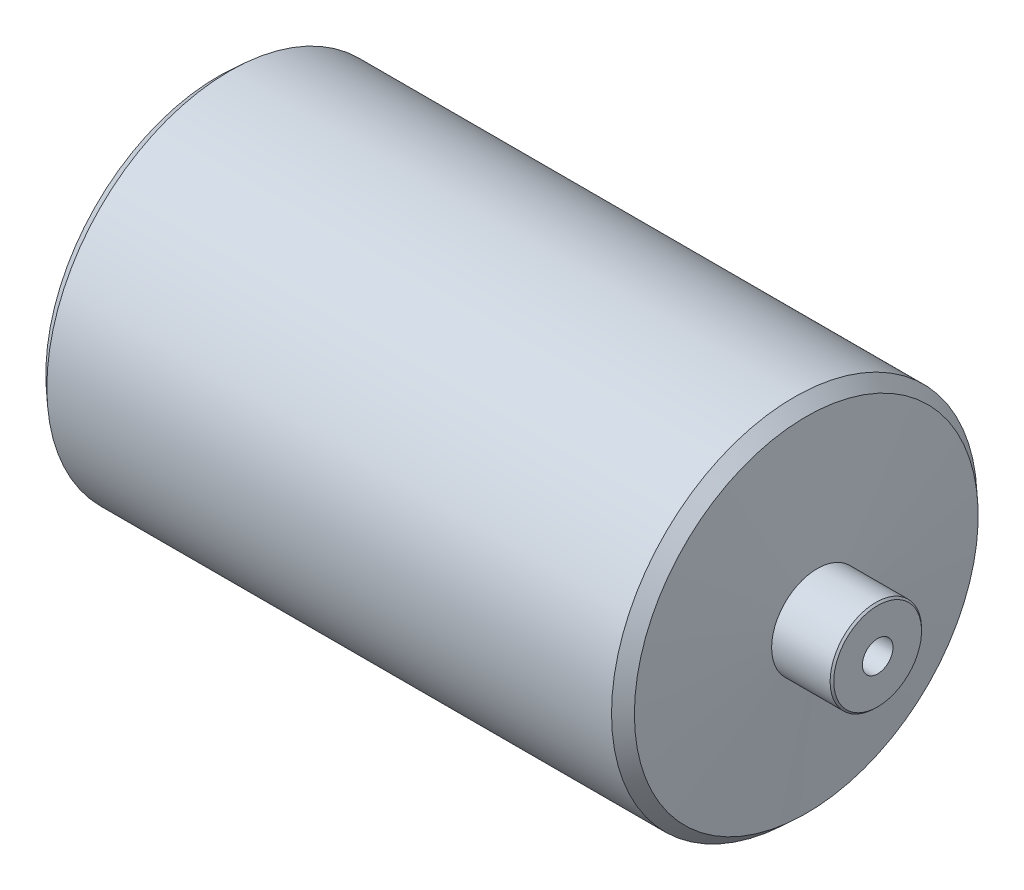
SolidWorks part; units mm, degrees
ref_plane "前基準面" through (0, 0, 0) normal (0, 0, 1) x (1, 0, 0)
ref_plane "上基準面" through (0, 0, 0) normal (0, 1, 0) x (1, 0, 0)
ref_plane "右基準面" through (0, 0, 0) normal (1, 0, 0) x (0, 0, -1)
ref_plane "平面1"
sketch "草圖1" plane through (0, 0, 0) normal (0, 0, 1) x (1, 0, 0)
  line L0 (0, 0) -> (0, 12.5)
  line L1 (0, 12.5) -> (16.5, 12.5)
  line L2 (16.5, 12.5) -> (19.7808, 50)
  line L3 (19.7808, 50) -> (180.2192, 50)
  line L4 (180.2192, 50) -> (183.5, 12.5)
  line L5 (183.5, 12.5) -> (200, 12.5)
  line L6 (200, 12.5) -> (200, 0)
  line L7 (200, 0) -> (0, 0)
  line L8 (0, 0) -> (200, 0) construction
  dimension "D1" = 12.5
  dimension "D2" = 200
  dimension "D3" = 12.5
  dimension "D4" = 16.5
  dimension "D5" = 16.5
  dimension "D6" = 95
  dimension "D7" = 95
  dimension "D8" = 50
revolve "迴轉1" add sketch "草圖1" angle 360 about L8
chamfer "倒角1" distance 3 distance2 3 2 edges at (180.2192, 0, 50) (19.7808, 0, 50)
chamfer "倒角2" distance 0.5 distance2 0.5 2 edges at (200, 0, 12.5) (0, 0, 12.5)
hole_wizard "孔1" positions "草圖3" profile "草圖2" legacy
sketch "草圖3" plane through (200, 0, 0) normal (1, 0, 0) x (0, 0, -1)
  point P1 (0, 0)
sketch "草圖2" plane through (200, 0, 0) normal (0, 1, 0) x (0, 0, -1)
  line L0 (0, 0) -> (0, 61.5164)
  line L1 (0, 61.5164) -> (4.188, 59)
  line L2 (4.188, 59) -> (4.188, 0)
  line L4 (4.188, 0) -> (0, 0)
  line L6 (0, 61.5164) -> (-4.188, 59) construction
  line L7 (0, -4.2442) -> (0, 117.3081) construction
  dimension "直徑" = 8.376
  dimension "深度" = 59
  dimension "導頭角度" = 118
cosmetic thread "裝飾螺紋線1"
hole_wizard "孔2" positions "草圖5" profile "草圖4" legacy
sketch "草圖5" plane through (0, 0, 0) normal (-1, 0, 0) x (0, 0, 1)
  point P1 (0, 0)
sketch "草圖4" plane through (0, 0, 0) normal (0, 1, 0) x (0, 0, 1)
  line L0 (0, 0) -> (0, 61.5164)
  line L1 (0, 61.5164) -> (4.188, 59)
  line L2 (4.188, 59) -> (4.188, 0)
  line L4 (4.188, 0) -> (0, 0)
  line L6 (0, 61.5164) -> (-4.188, 59) construction
  line L7 (0, -4.2442) -> (0, 117.3081) construction
  dimension "直徑" = 8.376
  dimension "深度" = 59
  dimension "導頭角度" = 118
cosmetic thread "裝飾螺紋線2"
